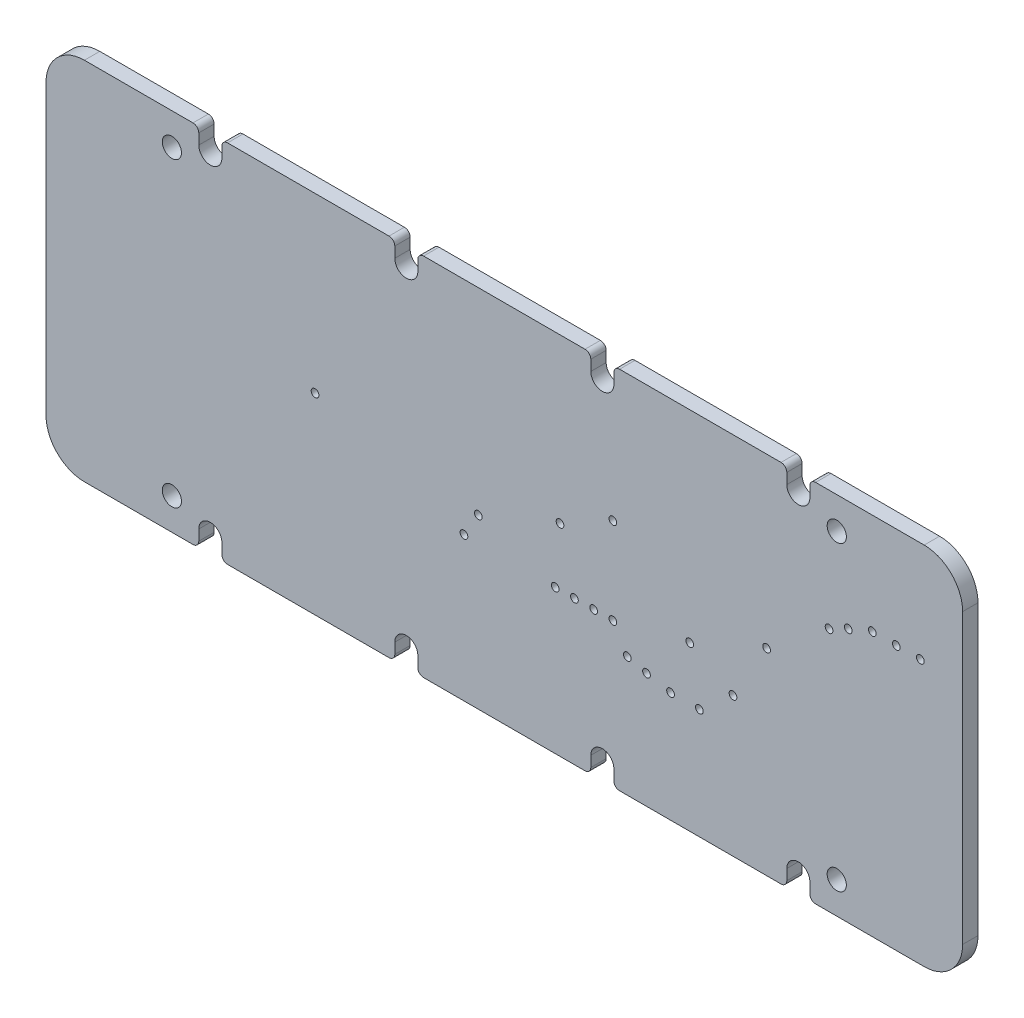
SolidWorks part; units mm, degrees
ref_plane "Front Plane" through (0, 0, 0) normal (0, 0, 1) x (1, 0, 0)
ref_plane "Top Plane" through (0, 0, 0) normal (0, 1, 0) x (1, 0, 0)
ref_plane "Right Plane" through (0, 0, 0) normal (1, 0, 0) x (0, 0, -1)
sketch "Sketch1" plane through (0, 0, 0) normal (0, 0, 1) x (1, 0, 0)
  line L0 (7.65, 0) -> (2, 0)
  line L1 (0, 2) -> (0, 17)
  line L2 (2, 19) -> (7.65, 19)
  line L3 (7.95, 18.7) -> (7.95, 18.15)
  line L4 (9.15, 18.15) -> (9.15, 18.7)
  line L5 (9.45, 19) -> (17.85, 19)
  line L6 (18.15, 18.7) -> (18.15, 18.15)
  line L7 (19.35, 18.15) -> (19.35, 18.7)
  line L8 (19.65, 19) -> (28.05, 19)
  line L9 (28.35, 18.7) -> (28.35, 18.15)
  line L10 (29.55, 18.15) -> (29.55, 18.7)
  line L11 (29.85, 19) -> (38.25, 19)
  line L12 (38.55, 18.7) -> (38.55, 18.15)
  line L13 (39.75, 18.15) -> (39.75, 18.7)
  line L14 (40.05, 19) -> (45.7, 19)
  line L15 (47.7, 17) -> (47.7, 2)
  line L16 (45.7, 0) -> (40.05, 0)
  line L17 (39.75, 0.3) -> (39.75, 0.85)
  line L18 (38.55, 0.85) -> (38.55, 0.3)
  line L19 (38.25, 0) -> (29.85, 0)
  line L20 (29.55, 0.3) -> (29.55, 0.85)
  line L21 (28.35, 0.85) -> (28.35, 0.3)
  line L22 (28.05, 0) -> (19.65, 0)
  line L23 (19.35, 0.3) -> (19.35, 0.85)
  line L24 (18.15, 0.85) -> (18.15, 0.3)
  line L25 (17.85, 0) -> (9.45, 0)
  line L26 (9.15, 0.3) -> (9.15, 0.85)
  line L27 (7.95, 0.85) -> (7.95, 0.3)
  arc A0 (2, 0) -> (0, 2) centre (2, 2) cw
  arc A1 (0, 17) -> (2, 19) centre (2, 17) cw
  arc A2 (7.65, 19) -> (7.95, 18.7) centre (7.65, 18.7) cw
  arc A3 (7.95, 18.15) -> (8.55, 17.55) centre (8.55, 18.15) ccw
  arc A4 (8.55, 17.55) -> (9.15, 18.15) centre (8.55, 18.15) ccw
  arc A5 (9.15, 18.7) -> (9.45, 19) centre (9.45, 18.7) cw
  arc A6 (17.85, 19) -> (18.15, 18.7) centre (17.85, 18.7) cw
  arc A7 (18.15, 18.15) -> (18.75, 17.55) centre (18.75, 18.15) ccw
  arc A8 (18.75, 17.55) -> (19.35, 18.15) centre (18.75, 18.15) ccw
  arc A9 (19.35, 18.7) -> (19.65, 19) centre (19.65, 18.7) cw
  arc A10 (28.05, 19) -> (28.35, 18.7) centre (28.05, 18.7) cw
  arc A11 (28.35, 18.15) -> (28.95, 17.55) centre (28.95, 18.15) ccw
  arc A12 (28.95, 17.55) -> (29.55, 18.15) centre (28.95, 18.15) ccw
  arc A13 (29.55, 18.7) -> (29.85, 19) centre (29.85, 18.7) cw
  arc A14 (38.25, 19) -> (38.55, 18.7) centre (38.25, 18.7) cw
  arc A15 (38.55, 18.15) -> (39.15, 17.55) centre (39.15, 18.15) ccw
  arc A16 (39.15, 17.55) -> (39.75, 18.15) centre (39.15, 18.15) ccw
  arc A17 (39.75, 18.7) -> (40.05, 19) centre (40.05, 18.7) cw
  arc A18 (45.7, 19) -> (47.7, 17) centre (45.7, 17) cw
  arc A19 (47.7, 2) -> (45.7, 0) centre (45.7, 2) cw
  arc A20 (40.05, 0) -> (39.75, 0.3) centre (40.05, 0.3) cw
  arc A21 (39.75, 0.85) -> (39.15, 1.45) centre (39.15, 0.85) ccw
  arc A22 (39.15, 1.45) -> (38.55, 0.85) centre (39.15, 0.85) ccw
  arc A23 (38.55, 0.3) -> (38.25, 0) centre (38.25, 0.3) cw
  arc A24 (29.85, 0) -> (29.55, 0.3) centre (29.85, 0.3) cw
  arc A25 (29.55, 0.85) -> (28.95, 1.45) centre (28.95, 0.85) ccw
  arc A26 (28.95, 1.45) -> (28.35, 0.85) centre (28.95, 0.85) ccw
  arc A27 (28.35, 0.3) -> (28.05, 0) centre (28.05, 0.3) cw
  arc A28 (19.65, 0) -> (19.35, 0.3) centre (19.65, 0.3) cw
  arc A29 (19.35, 0.85) -> (18.75, 1.45) centre (18.75, 0.85) ccw
  arc A30 (18.75, 1.45) -> (18.15, 0.85) centre (18.75, 0.85) ccw
  arc A31 (18.15, 0.3) -> (17.85, 0) centre (17.85, 0.3) cw
  arc A32 (9.45, 0) -> (9.15, 0.3) centre (9.45, 0.3) cw
  arc A33 (9.15, 0.85) -> (8.55, 1.45) centre (8.55, 0.85) ccw
  arc A34 (8.55, 1.45) -> (7.95, 0.85) centre (8.55, 0.85) ccw
  arc A35 (7.95, 0.3) -> (7.65, 0) centre (7.65, 0.3) cw
extrude "BOARD" add sketch "Sketch1" along normal blind 0.8 separate body
sketch "Sketch2" plane through (0, 0, 0) normal (0, 0, 1) x (1, 0, 0)
  circle A0 centre (6.55, 17.35) radius 0.5
  circle A1 centre (6.55, 1.65) radius 0.5
  circle A2 centre (41.15, 17.35) radius 0.5
  circle A3 centre (41.15, 1.65) radius 0.5
extrude "NON-PLATED HOLES" cut sketch "Sketch2" along normal through all
sketch "Sketch3" plane through (0, 0, 0) normal (0, 0, 1) x (1, 0, 0)
  circle A0 centre (37.5, 10.25) radius 0.2
  circle A1 centre (26.75, 10.5) radius 0.2
  circle A2 centre (14, 10) radius 0.2
  circle A3 centre (30.25, 6.25) radius 0.2
  circle A4 centre (31.25, 6) radius 0.2
  circle A5 centre (32.5, 5.75) radius 0.2
  circle A6 centre (34, 5.75) radius 0.2
  circle A7 centre (33.5, 8.5) radius 0.2
  circle A8 centre (35.75, 7.25) radius 0.2
  circle A9 centre (21.75, 7.5) radius 0.2
  circle A10 centre (22.5, 8.75) radius 0.2
  circle A11 centre (29.5, 7.5) radius 0.2
  circle A12 centre (28.5, 7.5) radius 0.2
  circle A13 centre (27.5, 7.5) radius 0.2
  circle A14 centre (26.5, 7.5) radius 0.2
  circle A15 centre (29.5, 12) radius 0.2
  circle A16 centre (40.75, 12.75) radius 0.2
  circle A17 centre (41.75, 13.25) radius 0.2
  circle A18 centre (43, 13.75) radius 0.2
  circle A19 centre (44.25, 13.75) radius 0.2
  circle A20 centre (45.5, 13.75) radius 0.2
extrude "PLATED HOLES" cut sketch "Sketch3" along normal through all
ref_plane "Plane1" through (0, 0, 150) normal (0, 0, 1) x (1, 0, 0)
